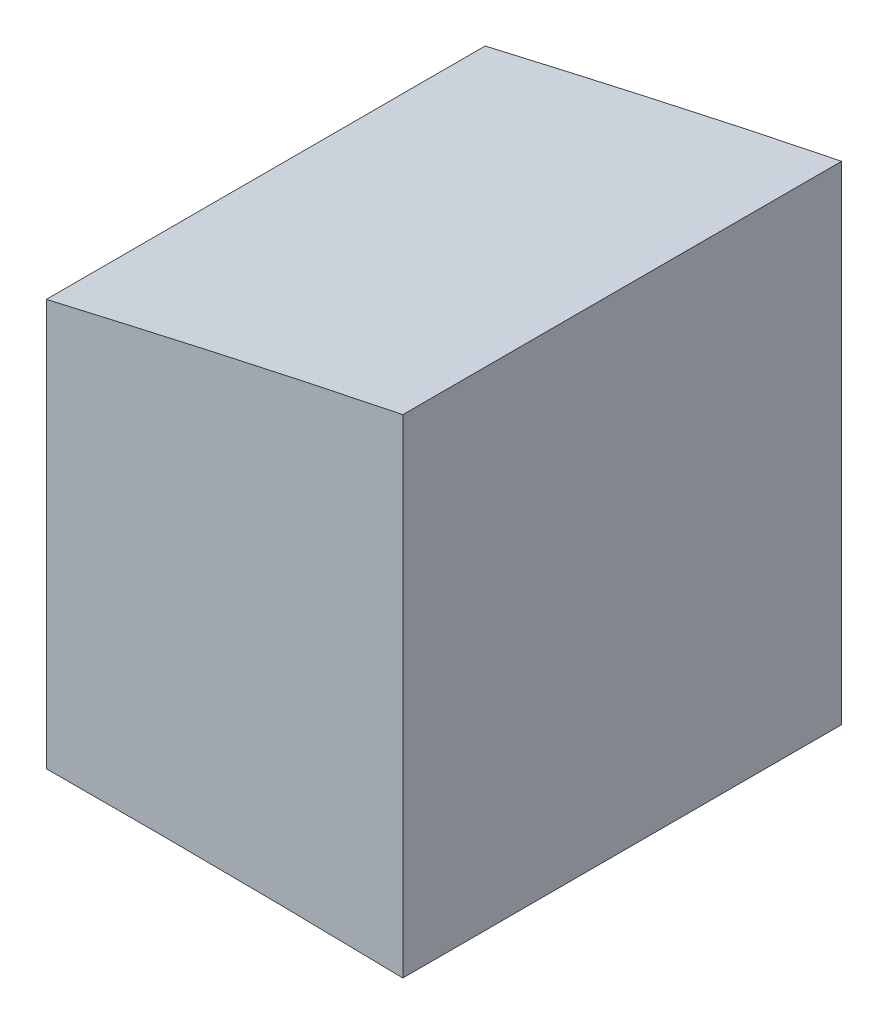
SolidWorks part; units mm, degrees
ref_plane "Front Plane" through (0, 0, 0) normal (0, 0, 1) x (1, 0, 0)
ref_plane "Top Plane" through (0, 0, 0) normal (0, 1, 0) x (1, 0, 0)
ref_plane "Right Plane" through (0, 0, 0) normal (1, 0, 0) x (0, 0, -1)
sketch "Sketch1" plane through (0, 0, 0) normal (0, 0, 1) x (1, 0, 0)
  line L0 (-66.007, 14.9523) -> (-66.007, -5.6347)
  circle A0 centre (63.517, -7.2283) radius 2.127
  circle A1 centre (-25.383, 13.0917) radius 2.127
  spline S0 degree 3 poles (76.217, -12.3083) (75.607, -6.7666) (69.7043, 1.1384) (56.4222, 10.2644) (36.9761, 19.3708) (8.7417, 24.8154) (-27.4552, 23.5667) (-52.3876, 18.1036) (-66.007, 14.9523) knots 0 0 0 0 0.086587 0.161737 0.268322 0.445157 0.638029 0.872371 0.872371 0.872371 0.872371
  spline S1 degree 3 poles (-66.007, -5.6347) (-44.594, -5.5392) (-13.013, -6.7241) (26.1367, -12.7509) (48.7653, -16.9008) (64.6834, -16.9691) (75.2906, -17.5225) (76.217, -12.3083) knots 0.133251 0.133251 0.133251 0.133251 0.51733 0.696667 0.84941 0.91952 1 1 1 1
extrude "Boss-Extrude1" add sketch "Sketch1" along normal blind 22.225
sketch "Sketch2" plane through (0, 0, 22.225) normal (0, 0, 1) x (1, 0, 0)
  line L1 (-47.9511, 30.6925) -> (167.5121, 30.6925)
  line L2 (-47.9511, 30.6925) -> (-47.9511, -22.6703)
  line L3 (-47.9511, -22.6703) -> (167.5121, -22.6703)
  line L4 (167.5121, 30.6925) -> (167.5121, -22.6703)
extrude "Cut-Extrude1" cut sketch "Sketch2" against normal blind 28.956
